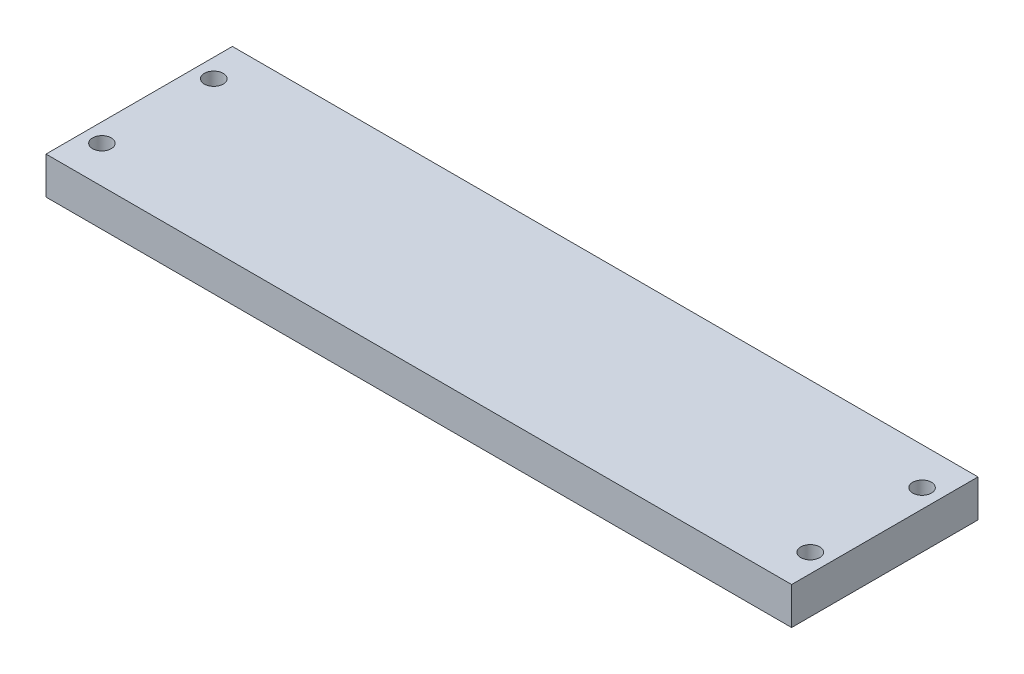
SolidWorks part; units mm, degrees
ref_plane "Front Plane" through (0, 0, 0) normal (0, 0, 1) x (1, 0, 0)
ref_plane "Top Plane" through (0, 0, 0) normal (0, 1, 0) x (1, 0, 0)
ref_plane "Right Plane" through (0, 0, 0) normal (1, 0, 0) x (0, 0, -1)
sketch "Sketch1" plane through (0, 0, 0) normal (0, 1, 0) x (1, 0, 0)
  line L1 (-63.5, -15.875) -> (63.5, -15.875)
  line L2 (-63.5, -15.875) -> (-63.5, 15.875)
  line L3 (-63.5, 15.875) -> (63.5, 15.875)
  line L4 (63.5, -15.875) -> (63.5, 15.875)
  line L5 (-63.5, -15.875) -> (63.5, 15.875) construction
  line L6 (-63.5, 15.875) -> (63.5, -15.875) construction
  point P0 (0, 0)
  dimension "D1" = 127
  dimension "D2" = 31.75
extrude "Boss-Extrude1" add sketch "Sketch1" along normal mid plane 6.35
sketch "Sketch2" plane through (0, -3.175, 0) normal (0, -1, 0) x (1, 0, 0)
  point P0 (-60.325, 9.525)
  point P1 (-60.325, -9.525)
  point P3 (60.325, 9.525)
  point P5 (60.325, -9.525)
hole_wizard "CSK for M3 Flat Head Machine Screw1" positions "Sketch3" profile "Sketch5" countersink size "M3" standard "ANSI Metric"
sketch "Sketch3" plane through (0, -3.175, 0) normal (0, -1, 0) x (-1, 0, 0)
  point P0 (60.325, -9.525)
  point P3 (60.325, 9.525)
  point P6 (-60.325, -9.525)
  point P9 (-60.325, 9.525)
sketch "Sketch5" plane through (-60.325, -3.175, 9.525) normal (1, 0, 0) x (0, 0, -1)
  line L0 (0, 0) -> (0, 13.6614)
  line L1 (0, 13.6614) -> (1.6, 12.7)
  line L2 (1.6, 12.7) -> (1.6, 1.55)
  line L3 (1.6, 1.55) -> (3.15, 0)
  line L5 (3.15, 0) -> (0, 0)
  line L6 (-1.6, 1.55) -> (-3.15, 0) construction
  line L10 (0, 13.6614) -> (-1.6, 12.7) construction
  line L11 (0, -6.35) -> (0, 107.95) construction
  dimension "Hole Dia." = 3.2
  dimension "Hole Depth" = 12.7
  dimension "Near C'Sink Dia." = 6.3
  dimension "Near C'Sink Angle" = 90
  dimension "Drill Angle" = 118
